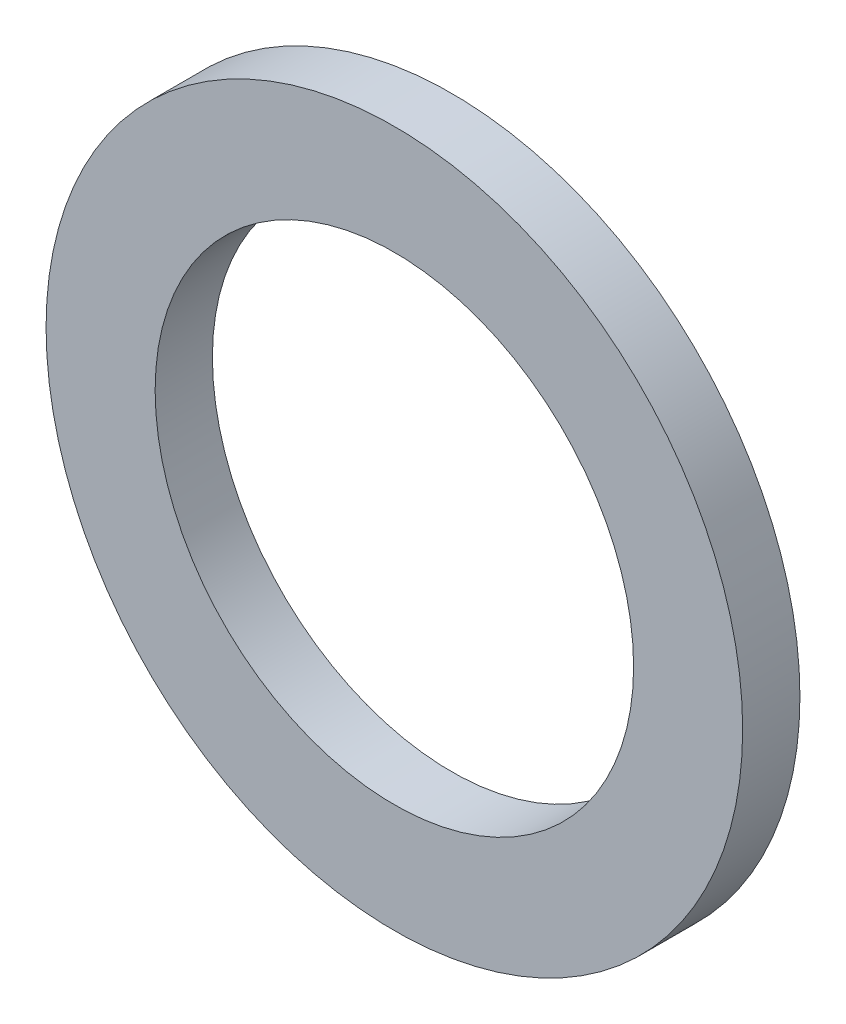
SolidWorks part; units mm, degrees
ref_plane "Front Plane" through (0, 0, 0) normal (0, 0, 1) x (1, 0, 0)
ref_plane "Top Plane" through (0, 0, 0) normal (0, 1, 0) x (1, 0, 0)
ref_plane "Right Plane" through (0, 0, 0) normal (1, 0, 0) x (0, 0, -1)
sketch "Sketch1" plane through (0, 0, 0) normal (0, 0, 1) x (1, 0, 0)
  circle A0 centre (0, 0) radius 6.4897
  circle A1 centre (0, 0) radius 4.4577
  dimension "D1" = 12.9794
  dimension "D2" = 8.9154
extrude "Boss-Extrude1" add sketch "Sketch1" along normal blind 1.0668
